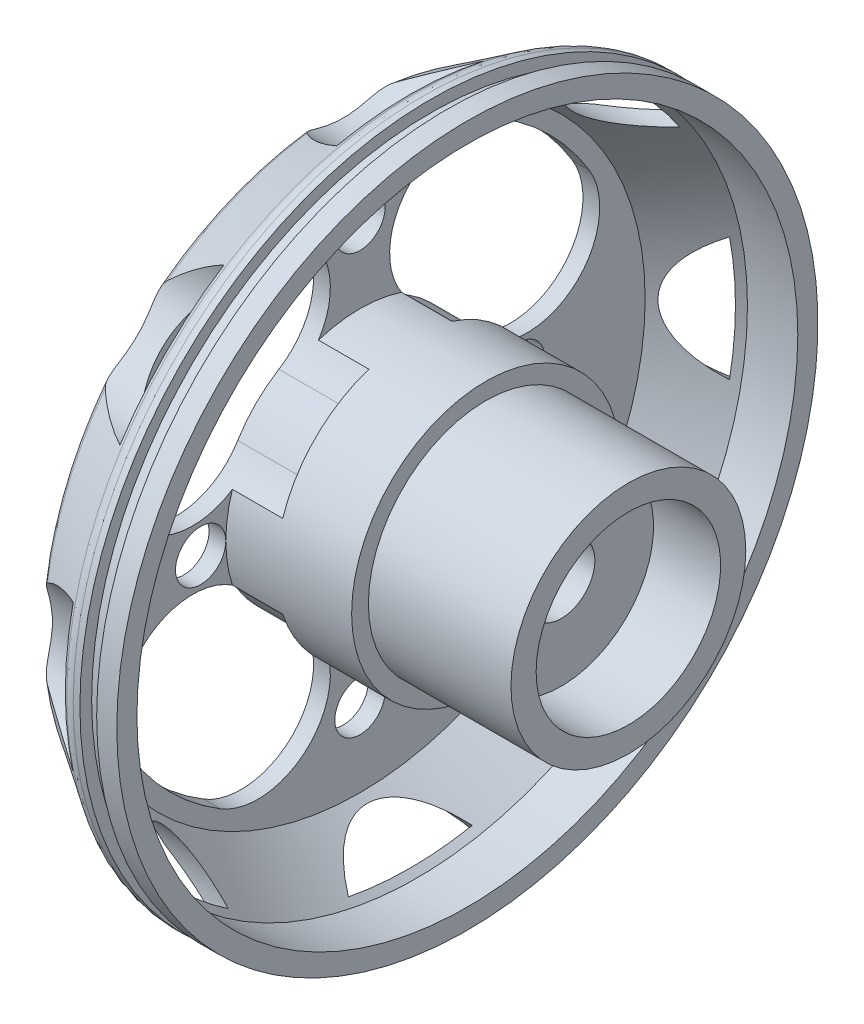
SolidWorks part; units mm, degrees
ref_plane "Front Plane" through (0, 0, 0) normal (0, 0, 1) x (1, 0, 0)
ref_plane "Top Plane" through (0, 0, 0) normal (0, 1, 0) x (1, 0, 0)
ref_plane "Right Plane" through (0, 0, 0) normal (1, 0, 0) x (0, 0, -1)
sketch "Sketch1" plane through (0, 0, 0) normal (0, 0, 1) x (1, 0, 0)
  line L0 (0, 0) -> (0, 23.6185) construction
  line L1 (0, 0) -> (30.1601, 0) construction
  line L2 (17, 5.5) -> (13, 5.5)
  line L3 (13, 5.5) -> (13, 2)
  line L4 (13, 2) -> (4, 2)
  line L5 (4, 2) -> (4, 5.5)
  line L6 (4, 5.5) -> (0, 5.5)
  line L7 (0, 5.5) -> (0, 18)
  line L8 (4.5, 20.9) -> (5.2, 20.9)
  line L9 (7.4, 20.9) -> (7.4, 19.7)
  line L10 (7.4, 19.7) -> (4.4, 19.7)
  line L11 (4.4, 19.7) -> (1, 17)
  line L12 (1, 17) -> (1, 8)
  line L13 (1, 8) -> (8.5, 8)
  line L14 (8.5, 8) -> (8.5, 7)
  line L15 (8.5, 7) -> (17, 7)
  line L16 (17, 7) -> (17, 5.5)
  line L17 (6.2, 20.9) -> (7.4, 20.9)
  line L19 (5.2, 20.9) -> (5.2, 20.2)
  line L20 (5.2, 20.2) -> (6.2, 20.2)
  line L21 (6.2, 20.9) -> (6.2, 20.2)
  arc A0 (0, 18) -> (4.5, 20.9) centre (-93.323, 167.753) ccw
  dimension "D19" = 176.4516
  dimension "D1" = 20.9
  dimension "D2" = 17
  dimension "D3" = 2
  dimension "D4" = 7
  dimension "D5" = 8
  dimension "D6" = 4
  dimension "D7" = 4.5
  dimension "D8" = 5.5
  dimension "D9" = 1
  dimension "D10" = 2.9
  dimension "D11" = 4.5
  dimension "D12" = 3
  dimension "D13" = 1.2
  dimension "D14" = 18
  dimension "D15" = 9
  dimension "D16" = 0.7
  dimension "D17" = 1
  dimension "D18" = 0.7
revolve "Revolve1" add sketch "Sketch1" angle 360 about L1
fillet "Fillet1" radius 1 2 edges at (4.5, 0, 20.9) (0, 0, 18)
sketch "Sketch2" plane through (0, 0, 0) normal (-1, 0, 0) x (0, 0, 1)
  line L0 (0, 20.7332) -> (0, 0) construction
  line L2 (0, 0) -> (14.6606, 14.6606) construction
  circle A0 centre (0, 0) radius 20.7332 construction
  arc A1 (9.9735, 6.0844) -> (6.0844, 9.9735) centre (0, 0) ccw construction
  arc A2 (13.6589, 8.3327) -> (8.3327, 13.6589) centre (0, 0) ccw
  arc A3 (6.2882, 3.8361) -> (3.8361, 6.2882) centre (0, 0) ccw
  arc A4 (6.2882, 3.8361) -> (13.6589, 8.3327) centre (9.9735, 6.0844) ccw
  arc A5 (8.3327, 13.6589) -> (3.8361, 6.2882) centre (6.0844, 9.9735) ccw
  arc A6 (6.0844, -9.9735) -> (9.9735, -6.0844) centre (0, 0) ccw construction
  arc A7 (8.3327, -13.6589) -> (13.6589, -8.3327) centre (0, 0) ccw
  arc A8 (3.8361, -6.2882) -> (6.2882, -3.8361) centre (0, 0) ccw
  arc A9 (3.8361, -6.2882) -> (8.3327, -13.6589) centre (6.0844, -9.9735) ccw
  arc A10 (13.6589, -8.3327) -> (6.2882, -3.8361) centre (9.9735, -6.0844) ccw
  arc A11 (-9.9735, -6.0844) -> (-6.0844, -9.9735) centre (0, 0) ccw construction
  arc A12 (-13.6589, -8.3327) -> (-8.3327, -13.6589) centre (0, 0) ccw
  arc A13 (-6.2882, -3.8361) -> (-3.8361, -6.2882) centre (0, 0) ccw
  arc A14 (-6.2882, -3.8361) -> (-13.6589, -8.3327) centre (-9.9735, -6.0844) ccw
  arc A15 (-8.3327, -13.6589) -> (-3.8361, -6.2882) centre (-6.0844, -9.9735) ccw
  arc A16 (-6.0844, 9.9735) -> (-9.9735, 6.0844) centre (0, 0) ccw construction
  arc A17 (-8.3327, 13.6589) -> (-13.6589, 8.3327) centre (0, 0) ccw
  arc A18 (-3.8361, 6.2882) -> (-6.2882, 3.8361) centre (0, 0) ccw
  arc A19 (-3.8361, 6.2882) -> (-8.3327, 13.6589) centre (-6.0844, 9.9735) ccw
  arc A20 (-13.6589, 8.3327) -> (-6.2882, 3.8361) centre (-9.9735, 6.0844) ccw
  arc A21 (11.1632, 17.4714) -> (17.4714, 11.1632) centre (15.7051, 15.7051) ccw
  arc A22 (17.4714, 11.1632) -> (11.1632, 17.4714) centre (0, 0) ccw
  arc A23 (20.2477, 4.4606) -> (20.2477, -4.4606) centre (22.2103, 0) ccw
  arc A24 (17.4714, -11.1632) -> (11.1632, -17.4714) centre (15.7051, -15.7051) ccw
  arc A25 (4.4606, -20.2477) -> (-4.4606, -20.2477) centre (0, -22.2103) ccw
  arc A26 (-11.1632, -17.4714) -> (-17.4714, -11.1632) centre (-15.7051, -15.7051) ccw
  arc A27 (-20.2477, -4.4606) -> (-20.2477, 4.4606) centre (-22.2103, 0) ccw
  arc A28 (-17.4714, 11.1632) -> (-11.1632, 17.4714) centre (-15.7051, 15.7051) ccw
  arc A29 (-4.4606, 20.2477) -> (4.4606, 20.2477) centre (0, 22.2103) ccw
  arc A30 (4.4606, 20.2477) -> (-4.4606, 20.2477) centre (0, 0) ccw
  arc A31 (-11.1632, 17.4714) -> (-17.4714, 11.1632) centre (0, 0) ccw
  arc A32 (-20.2477, 4.4606) -> (-20.2477, -4.4606) centre (0, 0) ccw
  arc A33 (-17.4714, -11.1632) -> (-11.1632, -17.4714) centre (0, 0) ccw
  arc A34 (-4.4606, -20.2477) -> (4.4606, -20.2477) centre (0, 0) ccw
  arc A35 (11.1632, -17.4714) -> (17.4714, -11.1632) centre (0, 0) ccw
  arc A36 (20.2477, -4.4606) -> (20.2477, 4.4606) centre (0, 0) ccw
  point P10 (8.2611, 8.2611)
  point P20 (8.2611, -8.2611)
  point P27 (-8.2611, -8.2611)
  point P34 (-8.2611, 8.2611)
  point P39 (0, 0)
  point P64 (0, 0)
  dimension "D3" = 16
  dimension "D1" = 45
  dimension "D2" = 5.5
  dimension "D4" = 4
  dimension "D5" = 8
extrude "Cut-Extrude2" cut sketch "Sketch2" against normal blind 4
sketch "Sketch3" plane through (0, 0, 0) normal (-1, 0, 0) x (0, 0, 1)
  circle A0 centre (0, 0) radius 12.5 construction
  circle A1 centre (0, 0) radius 9.5 construction
  circle A2 centre (0, 12.5) radius 1.5
  circle A3 centre (0, -12.5) radius 1.5
  circle A4 centre (9.5, 0) radius 1.5
  circle A5 centre (-9.5, 0) radius 1.5
  dimension "D1" = 19
  dimension "D2" = 25
  dimension "D3" = 3
extrude "Cut-Extrude3" cut sketch "Sketch3" against normal through all
